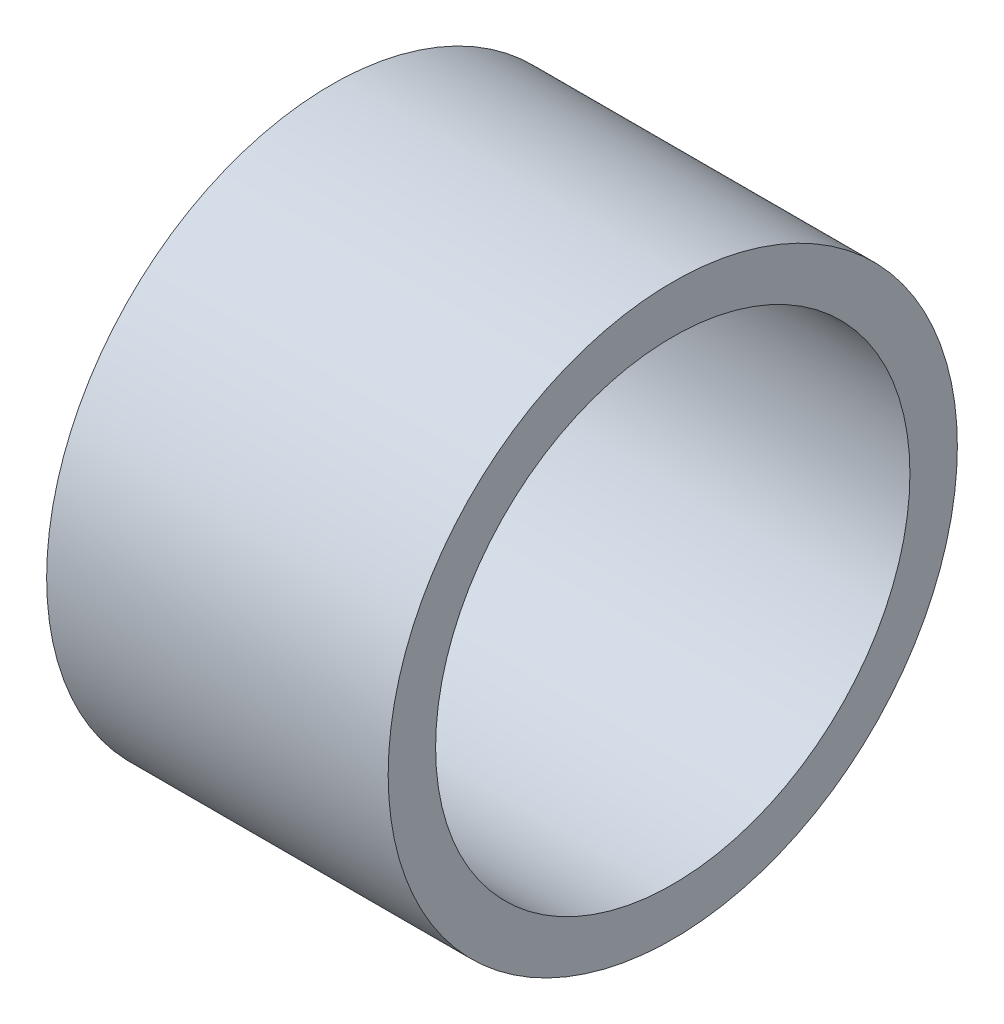
SolidWorks part; units mm, degrees
ref_plane "Front Plane" through (0, 0, 0) normal (1, 0, 0) x (0, 1, 0)
ref_plane "Top Plane" through (0, 0, 0) normal (0, 0, 1) x (0, 1, 0)
ref_plane "Right Plane" through (0, 0, 0) normal (0, 1, 0) x (-1, 0, 0)
sketch "Sketch2" plane through (0, 0, 0) normal (1, 0, 0) x (0, 1, 0)
  circle A0 centre (0, 0) radius 7.9375
  circle A1 centre (0, 0) radius 9.525
  dimension "D1" = 15.875
  dimension "D2" = 19.05
extrude "Boss-Extrude1" add sketch "Sketch2" along normal blind 11.43
